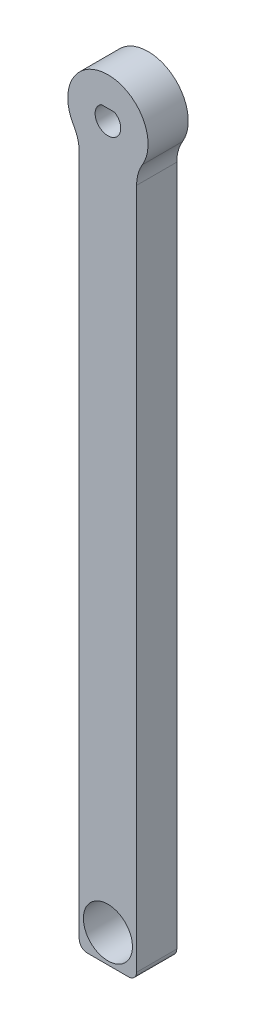
SolidWorks part; units mm, degrees
ref_plane "Front Plane" through (0, 0, 0) normal (0, 0, 1) x (1, 0, 0)
ref_plane "Top Plane" through (0, 0, 0) normal (0, 1, 0) x (1, 0, 0)
ref_plane "Right Plane" through (0, 0, 0) normal (1, 0, 0) x (0, 0, -1)
sketch "Sketch1" plane through (0, 0, 0) normal (0, 0, 1) x (1, 0, 0)
  line L0 (-1.6093, 2.52) -> (1.6093, 2.52)
  line L1 (-1.6666, 2.72) -> (1.6666, 2.72)
  arc A0 (-1.6186, 2.514) -> (1.6093, 2.52) centre (0, 0) ccw
  arc A1 (-1.6666, 2.72) -> (1.6666, 2.72) centre (0, 0) ccw
  circle A2 centre (0, 0) radius 10
  arc A3 (-1.6093, 2.52) -> (1.6093, 2.52) centre (0, 0) ccw construction
  dimension "D1" = 5.98
  dimension "D4" = 20
  dimension "D2" = 2.52
  dimension "D3" = 0.2
extrude "Boss-Extrude1" add sketch "Sketch1" along normal blind 10 contours A2 A1 L1
sketch "Sketch2" plane through (0, 0, 0) normal (0, 0, -1) x (-1, 0, 0)
  line L5 (-10, -7) -> (10, -7)
  line L6 (-10, -7) -> (-10, -10)
  line L7 (-10, -10) -> (10, -10)
  line L8 (10, -7) -> (10, -10)
  circle A1 centre (0, 0) radius 10
  circle A2 centre (0, 0) radius 10
  circle M8 centre (0, 0) radius 10
  dimension "D2" = 3
  dimension "D1" = 0
extrude "Cut-Extrude1" cut sketch "Sketch2" against normal blind 10 contours L5 M8
sketch "Sketch3" plane through (0, -7, 0) normal (0, -1, 0) x (1, 0, 0)
  line L4 (-7.1414, 0) -> (7.1414, 0)
  line L5 (7.1414, 0) -> (7.1414, 10)
  line L6 (7.1414, 10) -> (-7.1414, 10)
  line L7 (-7.1414, 10) -> (-7.1414, 0)
  line L8 (-7.1414, 0) -> (7.1414, 0)
  line L9 (7.1414, 0) -> (7.1414, 10)
  line L10 (7.1414, 10) -> (-7.1414, 10)
  line L11 (-7.1414, 10) -> (-7.1414, 0)
  dimension "D1" = 0
extrude "Boss-Extrude2" add sketch "Sketch3" along normal blind 175
sketch "Sketch4" plane through (0, 0, 0) normal (0, 0, -1) x (-1, 0, 0)
  line L0 (7.1414, -182) -> (-7.1414, -182) construction
  circle A0 centre (0, -175) radius 6.11
  dimension "D1" = 12.22
  dimension "D2" = 7
extrude "Cut-Extrude2" cut sketch "Sketch4" against normal blind 10
fillet "Fillet1" radius 10 2 edges at (-7.1414, -7, 5) (7.1414, -7, 5)
fillet "Fillet2" radius 2 2 edges at (-7.1414, -182, 5) (7.1414, -182, 5)
